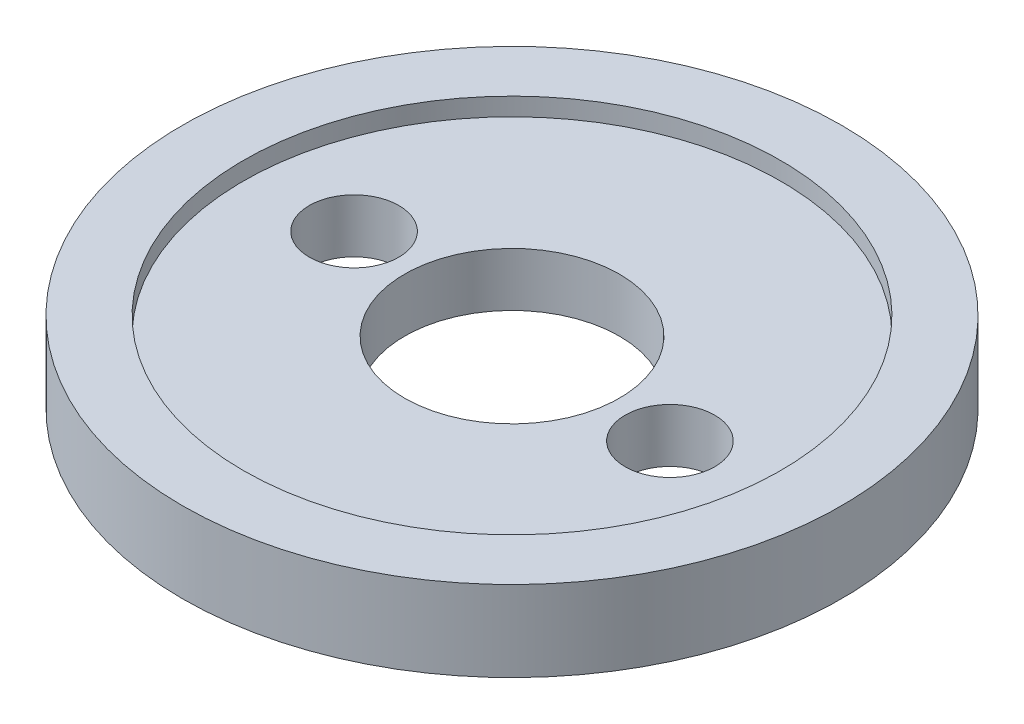
SolidWorks part; units mm, degrees
ref_plane "Front Plane" through (0, 0, 0) normal (0, 0, 1) x (1, 0, 0)
ref_plane "Top Plane" through (0, 0, 0) normal (0, 1, 0) x (1, 0, 0)
ref_plane "Right Plane" through (0, 0, 0) normal (1, 0, 0) x (0, 0, -1)
sketch "Sketch1" plane through (0, 0, 0) normal (0, 1, 0) x (1, 0, 0)
  circle A0 centre (0, 0) radius 18.4
extrude "Boss-Extrude1" add sketch "Sketch1" along normal blind 4.5
sketch "Sketch2" plane through (0, 4.5, 0) normal (0, 1, 0) x (1, 0, 0)
  circle A0 centre (0, 0) radius 15
extrude "Cut-Extrude1" cut sketch "Sketch2" against normal blind 1
sketch "Sketch3" plane through (0, 0, 0) normal (0, -1, 0) x (1, 0, 0)
  circle A0 centre (-9.4771, -0.6586) radius 2.5
  circle A1 centre (9.4771, 0.6586) radius 2.5
extrude "Cut-Extrude2" cut sketch "Sketch3" against normal through all
sketch "Sketch4" plane through (0, 0, 0) normal (0, -1, 0) x (1, 0, 0)
  circle A0 centre (0, 0) radius 15
extrude "Cut-Extrude3" cut sketch "Sketch4" against normal blind 0.5
sketch "Sketch5" plane through (0, 3.5, 0) normal (0, 1, 0) x (1, 0, 0)
  circle A0 centre (0, 0) radius 6
extrude "Cut-Extrude4" cut sketch "Sketch5" against normal through all
